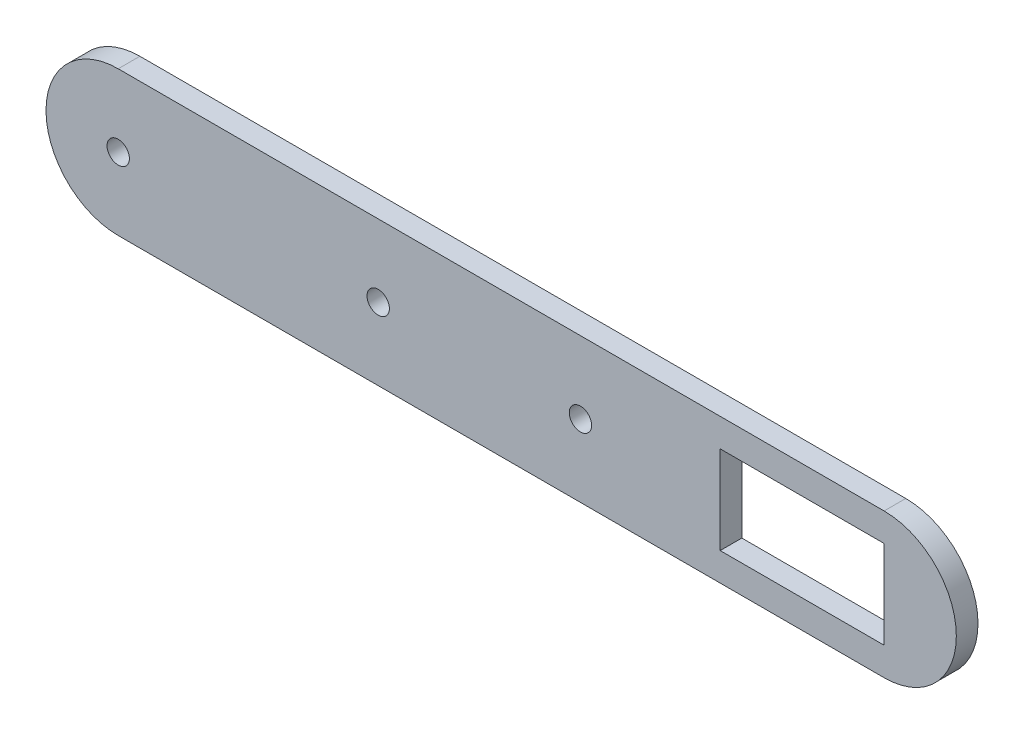
SolidWorks part; units mm, degrees
ref_plane "Front Plane" through (0, 0, 0) normal (0, 0, 1) x (1, 0, 0)
ref_plane "Top Plane" through (0, 0, 0) normal (0, 1, 0) x (1, 0, 0)
ref_plane "Right Plane" through (0, 0, 0) normal (1, 0, 0) x (0, 0, -1)
sketch "Sketch1" plane through (0, 0, 0) normal (0, 0, 1) x (1, 0, 0)
  line L0 (-58.0586, 14.1911) -> (47.9914, 14.1911) construction
  line L1 (-58.0586, 24.1911) -> (47.9914, 24.1911)
  line L2 (-58.0586, 4.1911) -> (47.9914, 4.1911)
  arc A0 (-58.0586, 24.1911) -> (-58.0586, 4.1911) centre (-58.0586, 14.1911) ccw
  arc A1 (47.9914, 4.1911) -> (47.9914, 24.1911) centre (47.9914, 14.1911) ccw
  point P2 (-5.0336, 14.1911)
extrude "Boss-Extrude1" add sketch "Sketch1" along normal blind 3
sketch "Sketch3" plane through (0, 0, 3) normal (0, 0, 1) x (1, 0, 0)
  circle A0 centre (-58.0586, 14.1911) radius 1.55
  arc A1 (-58.0586, 24.1911) -> (-58.0586, 4.1911) centre (-58.0586, 14.1911) ccw construction
extrude "Cut-Extrude2" cut sketch "Sketch3" against normal blind 3 contours A0
sketch "Sketch4" plane through (9.9795, 1.4333, 3) normal (0, 0, 1) x (1, 0, 0)
  line L0 (-68.0381, 2.7578) -> (38.0119, 2.7578) construction
  circle A0 centre (-4.0381, 12.7578) radius 1.55
  arc A2 (38.0119, 2.7578) -> (38.0119, 22.7578) centre (38.0119, 12.7578) ccw construction
  dimension "D1" = 10
  dimension "D2" = 42.05
extrude "Cut-Extrude4" cut sketch "Sketch4" against normal blind 3
sketch "Sketch5" plane through (-9.9795, 1.4333, 0) normal (0, 0, -1) x (-1, 0, 0)
  line L0 (-57.9708, 22.7578) -> (48.0792, 22.7578) construction
  circle A0 centre (12.0792, 12.7578) radius 1.55
  arc A2 (48.0792, 2.7578) -> (48.0792, 22.7578) centre (48.0792, 12.7578) ccw construction
  dimension "D1" = 10
  dimension "D2" = 36
extrude "Cut-Extrude6" cut sketch "Sketch5" against normal blind 3
sketch "Sketch6" plane through (0, 0, 3) normal (0, 0, 1) x (1, 0, 0)
  line L0 (47.9914, 24.1911) -> (-58.0586, 24.1911) construction
  line L1 (25.2914, 20.2911) -> (47.9914, 20.2911)
  line L2 (25.2914, 20.2911) -> (25.2914, 8.0911)
  line L3 (25.2914, 8.0911) -> (47.9914, 8.0911)
  line L4 (47.9914, 20.2911) -> (47.9914, 8.0911)
  arc A2 (47.9914, 4.1911) -> (47.9914, 24.1911) centre (47.9914, 14.1911) ccw construction
  point P7 (47.9914, 14.1911)
  point P10 (57.9914, 14.1911)
  dimension "D1" = 10
  dimension "D2" = 10
  dimension "D3" = 22.7
  dimension "D4" = 12.2
extrude "Cut-Extrude7" cut sketch "Sketch6" against normal blind 3
